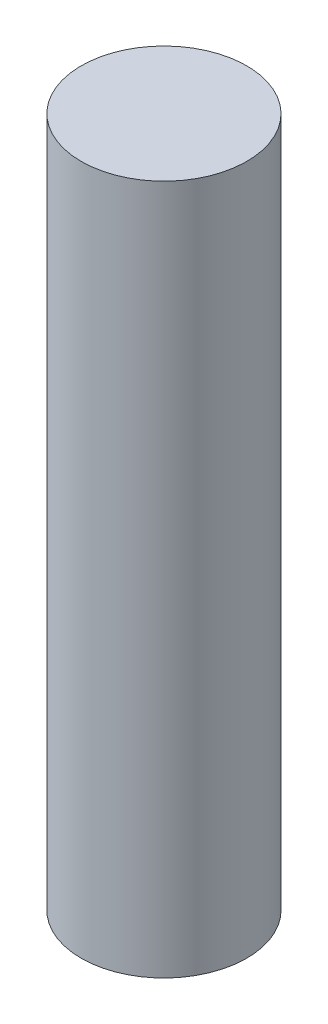
SolidWorks part; units mm, degrees
ref_plane "Plano frontal" through (0, 0, 0) normal (0, 0, 1) x (1, 0, 0)
ref_plane "Plano superior" through (0, 0, 0) normal (0, 1, 0) x (1, 0, 0)
ref_plane "Plano direito" through (0, 0, 0) normal (1, 0, 0) x (0, 0, -1)
sketch "Esboço1" plane through (0, 0, 0) normal (0, 1, 0) x (1, 0, 0)
  circle A0 centre (0, 0) radius 30
  dimension "D1" = 60
extrude "Ressalto-extrusão1" add sketch "Esboço1" along normal blind 250
